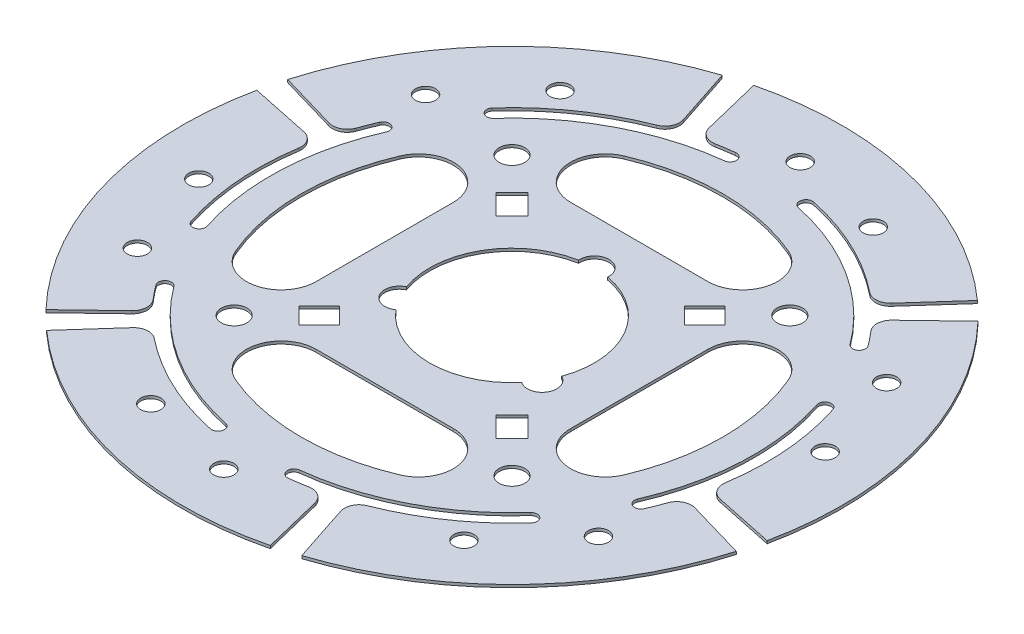
SolidWorks part; units mm, degrees
ref_plane "Front" through (0, 0, 0) normal (0, 0, 1) x (1, 0, 0)
ref_plane "Top" through (0, 0, 0) normal (0, 1, 0) x (1, 0, 0)
ref_plane "Right" through (0, 0, 0) normal (1, 0, 0) x (0, 0, -1)
sketch "Sketch1 layout" plane through (0, 0, 0) normal (0, 1, 0) x (1, 0, 0)
  line L0 (0, 0) -> (0, 90) construction
  line L1 (0, 0) -> (-26.3044, 26.3044) construction
  line L2 (-18.75, 44.25) -> (18.75, 44.25) construction
  line L3 (-18.75, 53.75) -> (18.75, 53.75) construction
  line L4 (-18.75, 34.75) -> (18.75, 34.75) construction
  line L5 (18.75, 34.75) -> (-18.75, 34.75)
  line L6 (0, 0.0636) -> (60, 67.082) construction
  line L7 (60, 67.082) -> (65, 62.2495) construction
  line L8 (65, 62.2495) -> (0, 0) construction
  line L9 (60, 67.082) -> (46.3261, 51.8087)
  line L10 (65, 62.2495) -> (50.1944, 48.0704)
  circle A0 centre (0, 0) radius 22.5
  circle A1 centre (0, 0) radius 67.75 construction
  circle A2 centre (0, 0) radius 75.75 construction
  circle A3 centre (0, 0) radius 90
  arc A4 (-18.75, 53.75) -> (-18.75, 34.75) centre (-18.75, 44.25) ccw construction
  arc A5 (18.75, 34.75) -> (18.75, 53.75) centre (18.75, 44.25) ccw construction
  arc A6 (-22.4609, 52.9952) -> (22.4609, 52.9952) centre (0, 0.0636) cw
  arc A7 (-22.4609, 52.9952) -> (-18.75, 34.75) centre (-18.75, 44.25) ccw
  arc A8 (22.4609, 52.9952) -> (18.75, 34.75) centre (18.75, 44.25) cw
  arc A9 (14, 66.2877) -> (54.4049, 40.3754) centre (0, 0) cw construction
  arc A10 (55.8101, 41.4183) -> (14.3616, 68) centre (0, 0) ccw
  arc A11 (52.9996, 39.3325) -> (13.6384, 64.5755) centre (0, 0) ccw
  arc A12 (52.9996, 39.3325) -> (55.8101, 41.4183) centre (54.4049, 40.3754) ccw
  arc A13 (14.3616, 68) -> (13.6384, 64.5755) centre (14, 66.2877) ccw
  circle A14 centre (0, 22.5) radius 4
  circle A15 centre (19.4856, -11.25) radius 4
  circle A16 centre (-19.4856, -11.25) radius 4
  point P6 (0, 44.25)
  point P25 (36.5741, 57.0298)
  point P42 (0, 0)
  dimension "D1" = 45
  dimension "D2" = 151.5
  dimension "D3" = 135.5
  dimension "D4" = 180
  dimension "D10" = 57.5
  dimension "D12" = 1.75
  dimension "D16" = 8
  dimension "D5" = 45
  dimension "D6" = 37.2
  dimension "D7" = 44.25
  dimension "D8" = 19
  dimension "D9" = 37.5
  dimension "D11" = 14
  dimension "D13" = 48
  dimension "D14" = 60
  dimension "D15" = 65
  dimension "D17" = 3
sketch "Sketch2" plane through (0, 0, 0) normal (0, 1, 0) x (1, 0, 0)
  circle A0 centre (-19.4856, -11.25) radius 4 construction
  circle A1 centre (19.4856, -11.25) radius 4 construction
  circle A2 centre (0, 22.5) radius 4 construction
  circle A3 centre (0, 0) radius 22.5 construction
  circle A4 centre (0, 0) radius 90 construction
  circle A5 centre (-19.4856, -11.25) radius 4
  circle A6 centre (19.4856, -11.25) radius 4
  circle A7 centre (0, 22.5) radius 4
  circle A8 centre (0, 0) radius 22.5
  circle A9 centre (0, 0) radius 90
extrude "Boss-Extrude1" add sketch "Sketch2" along normal blind 0.75 contours A9 A8 A6 A5 A7
sketch "Sketch3" plane through (0, 0.75, 0) normal (0, 1, 0) x (1, 0, 0)
  line L0 (18.75, 34.75) -> (-18.75, 34.75) construction
  line L1 (18.75, 34.75) -> (-18.75, 34.75)
  arc A0 (-22.4609, 52.9952) -> (-18.75, 34.75) centre (-18.75, 44.25) ccw construction
  arc A1 (18.75, 34.75) -> (22.4609, 52.9952) centre (18.75, 44.25) ccw construction
  arc A2 (22.4609, 52.9952) -> (-22.4609, 52.9952) centre (0, 0.0636) ccw construction
  arc A3 (-22.4609, 52.9952) -> (-18.75, 34.75) centre (-18.75, 44.25) ccw
  arc A4 (18.75, 34.75) -> (22.4609, 52.9952) centre (18.75, 44.25) ccw
  arc A5 (22.4609, 52.9952) -> (-22.4609, 52.9952) centre (0, 0.0636) ccw
extrude "Cut-Extrude1" cut sketch "Sketch3" against normal blind 0.75
sketch "Sketch4" plane through (0, 0.75, 0) normal (0, 1, 0) x (1, 0, 0)
  line L0 (65, 62.2495) -> (50.1944, 48.0704) construction
  line L1 (60, 67.082) -> (46.3261, 51.8087) construction
  line L2 (65, 62.2495) -> (50.1944, 48.0704)
  line L3 (60, 67.082) -> (46.3261, 51.8087)
  arc A0 (52.9996, 39.3325) -> (55.8101, 41.4183) centre (54.4049, 40.3754) ccw construction
  arc A1 (52.9996, 39.3325) -> (55.8101, 41.4183) centre (54.4049, 40.3754) ccw
  arc A2 (52.9996, 39.3325) -> (13.6384, 64.5755) centre (0, 0) ccw construction
  arc A3 (52.9996, 39.3325) -> (13.6384, 64.5755) centre (0, 0) ccw
  arc A4 (14.3616, 68) -> (13.6384, 64.5755) centre (14, 66.2877) ccw construction
  arc A5 (14.3616, 68) -> (13.6384, 64.5755) centre (14, 66.2877) ccw
  arc A6 (14.3616, 68) -> (46.3261, 51.8087) centre (0, 0) cw
  arc A7 (50.1944, 48.0704) -> (55.8101, 41.4183) centre (0, 0) cw
extrude "Cut-Extrude2" cut sketch "Sketch4" against normal blind 0.75 and the other way through all
sketch "Sketch5" plane through (0, 0.75, 0) normal (0, 1, 0) x (1, 0, 0)
  line L0 (-21.3369, 25.7564) -> (-26.8524, 31.2718)
  line L1 (-21.3369, 25.7564) -> (-25.7564, 21.3369)
  line L2 (-26.8524, 31.2718) -> (-31.2718, 26.8524)
  line L3 (-25.7564, 21.3369) -> (-31.2718, 26.8524)
  line L4 (-21.3369, 25.7564) -> (-31.2718, 26.8524) construction
  line L5 (-26.8524, 31.2718) -> (-25.7564, 21.3369) construction
  line L6 (0, 0) -> (-26.3044, 26.3044) construction
  point P1 (-26.3044, 26.3044)
  dimension "D1" = 6.25
  dimension "D2" = 7.8
extrude "Cut-Extrude3" cut sketch "Sketch5" against normal blind 0.75
pattern_circular "CirPattern1" count 4 over 360 about axis through (0, 0, 0) along (0, 1, 0) of "Cut-Extrude1", "Cut-Extrude3"
fillet "Fillet1" radius 4 2 edges at (46.3261, 0.375, -51.8087) (50.1944, 0.375, -48.0704)
pattern_circular "CirPattern3" count 6 over 360 about axis through (0, 0, 0) along (0, 1, 0) of "Cut-Extrude2", "Fillet1"
sketch "Sketch6" plane through (0, 0.75, 0) normal (0, 1, 0) x (1, 0, 0)
  line L0 (0, 0) -> (-26.3044, 26.3044) construction
  circle A0 centre (-36.8608, 38.9821) radius 3.5
  circle A1 centre (38.2321, 37.6108) radius 3.5
  circle A2 centre (36.8608, -37.4821) radius 3.5
  circle A3 centre (-38.2321, -36.1108) radius 3.5
  point P14 (0, 0.75)
  dimension "D1" = 7
  dimension "D2" = 1.5
  dimension "D3" = 53.65
  dimension "D4" = 4
sketch "Sketch8" plane through (0, 0, 0) normal (0, -1, 0) x (1, 0, 0)
  circle A0 centre (-3, 75.6906) radius 2.75
  circle A1 centre (-28.4174, 70.2176) radius 2.75
extrude "Cut-Extrude6" cut sketch "Sketch8" against normal blind 10
pattern_circular "CirPattern5" count 6 over 360 about axis through (0, 0, 0) along (0, 1, 0) of "Cut-Extrude6"
sketch "Sketch10" plane through (0, 0.75, 0) normal (0, 1, 0) x (1, 0, 0)
  circle A0 centre (37.9363, 37.9363) radius 3.5
extrude "Cut-Extrude8" cut sketch "Sketch10" against normal through all
pattern_circular "CirPattern6" count 4 over 360 about axis through (0, 0, 0) along (0, 1, 0) of "Cut-Extrude8"
